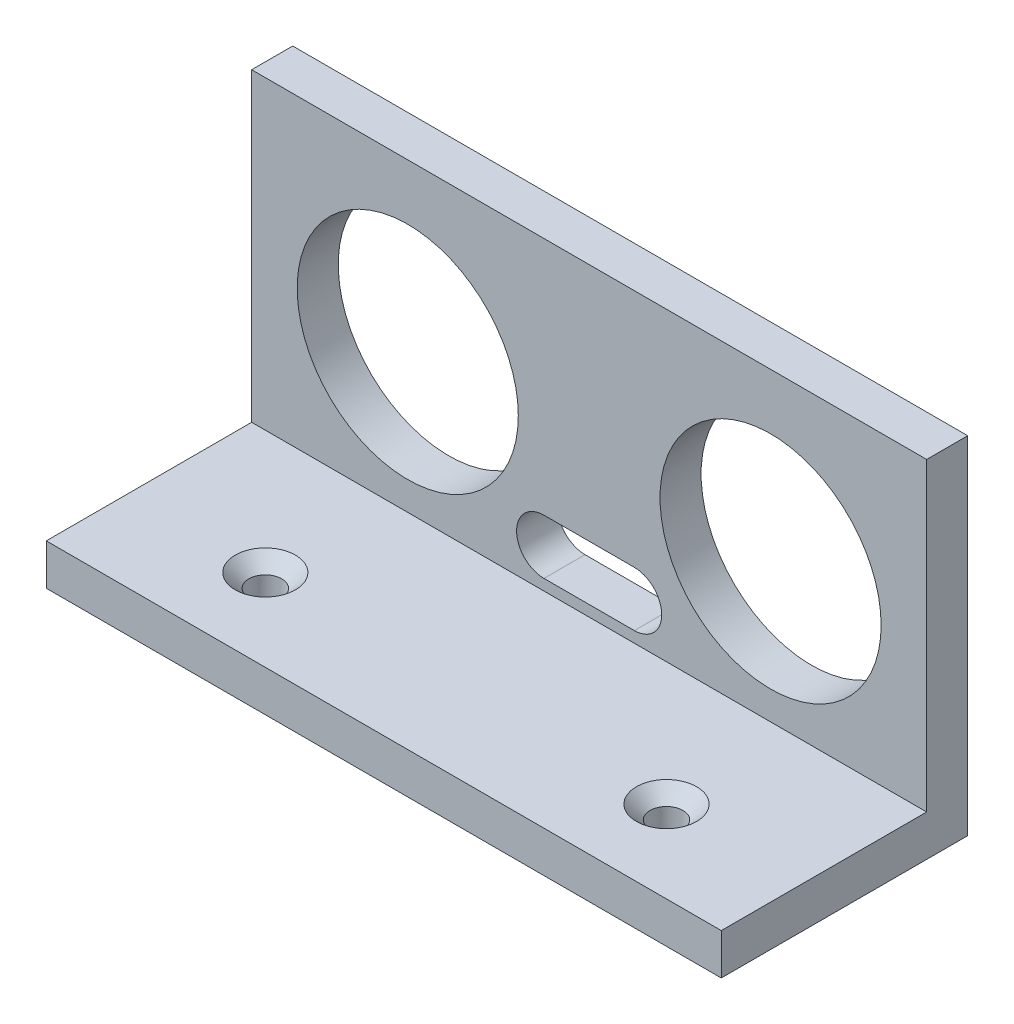
SolidWorks part; units mm, degrees
ref_plane "Front Plane" through (0, 0, 0) normal (0, 0, 1) x (1, 0, 0)
ref_plane "Top Plane" through (0, 0, 0) normal (0, 1, 0) x (1, 0, 0)
ref_plane "Right Plane" through (0, 0, 0) normal (1, 0, 0) x (0, 0, -1)
sketch "Sketch1" plane through (0, 0, 0) normal (0, 0, 1) x (1, 0, 0)
  line L1 (-24.65, -12.65) -> (24.65, -12.65)
  line L2 (-24.65, -12.65) -> (-24.65, 12.65)
  line L3 (-24.65, 12.65) -> (24.65, 12.65)
  line L4 (24.65, -12.65) -> (24.65, 12.65)
  line L5 (-24.65, -12.65) -> (24.65, 12.65) construction
  line L6 (-24.65, 12.65) -> (24.65, -12.65) construction
  point P0 (0, 0)
  dimension "D1" = 49.3
  dimension "D2" = 25.3
extrude "Boss-Extrude1" add sketch "Sketch1" along normal mid plane 3
sketch "Sketch4" plane through (0, 0, 1.5) normal (0, 0, 1) x (1, 0, 0)
  line L0 (-24.65, 12.65) -> (-24.65, -12.65) construction
  line L1 (-24.65, -12.65) -> (24.65, -12.65)
  line L2 (-24.65, -12.65) -> (-24.65, -9.65)
  line L3 (-24.65, -9.65) -> (24.65, -9.65)
  line L4 (24.65, -12.65) -> (24.65, -9.65)
  line L5 (-24.65, -12.65) -> (24.65, -9.65) construction
  line L6 (-24.65, -9.65) -> (24.65, -12.65) construction
  line L7 (24.65, -12.65) -> (24.65, 12.65) construction
  line L8 (-24.65, -12.65) -> (24.65, -12.65) construction
  point P0 (0, -11.15)
  dimension "D1" = 3
extrude "Boss-Extrude2" add sketch "Sketch4" along normal blind 15
sketch "Sketch7" plane through (0, -9.65, 0) normal (0, 1, 0) x (1, 0, 0)
  line L0 (0, 8.0909) -> (0, -21.0215) construction
  line L1 (-24.65, -16.5) -> (-24.65, -1.5) construction
  line L2 (24.65, -16.5) -> (-24.65, -16.5) construction
  point P0 (-14.65, -10.5)
  point P16 (14.65, -10.5)
  dimension "D1" = 10
  dimension "D2" = 6
hole_wizard "CSK for M2 Countersunk Flat Head Screw1" positions "Sketch7" profile "Sketch6" countersink size "M2" standard "ISO" end condition through all
sketch "Sketch6" plane through (-14.65, -9.65, 10.5) normal (1, 0, 0) x (0, 0, 1)
  line L0 (0, 0) -> (0, 3)
  line L1 (0, 3) -> (1.2, 3)
  line L2 (1.2, 3) -> (1.2, 1)
  line L3 (1.2, 1) -> (2.2, 0)
  line L5 (2.2, 0) -> (0, 0)
  line L6 (-1.2, 1) -> (-2.2, 0) construction
  line L11 (0, -6.35) -> (0, 107.95) construction
  dimension "Thru Hole Dia." = 2.4
  dimension "Thru Hole Depth" = 3
  dimension "Near C'Sink Dia." = 4.4
  dimension "Near C'Sink Angle" = 90
sketch "Sketch8" plane through (0, 0, 1.5) normal (0, 0, 1) x (1, 0, 0)
  line L0 (0, 16.9548) -> (0, -17.7543) construction
  line L1 (-24.65, 12.65) -> (-24.65, -9.65) construction
  line L2 (24.65, -9.65) -> (-24.65, -9.65) construction
  line L3 (-3.3, -4.85) -> (3.3, -4.85)
  line L5 (3.3, -8.85) -> (-3.3, -8.85)
  circle A0 centre (-13.25, 0.5) radius 8.075
  circle A1 centre (13.25, 0.5) radius 8.075
  arc A2 (3.3, -4.85) -> (3.3, -8.85) centre (3.3, -6.85) cw
  arc A3 (-3.3, -4.85) -> (-3.3, -8.85) centre (-3.3, -6.85) ccw
  point P17 (0, -8.85)
  point P19 (0, -4.85)
  dimension "D1" = 16.15
  dimension "D4" = 3.3
  dimension "D6" = 0.8
  dimension "D2" = 11.4
  dimension "D3" = 10.15
  dimension "D5" = 4
extrude "Cut-Extrude1" cut sketch "Sketch8" against normal up to next
